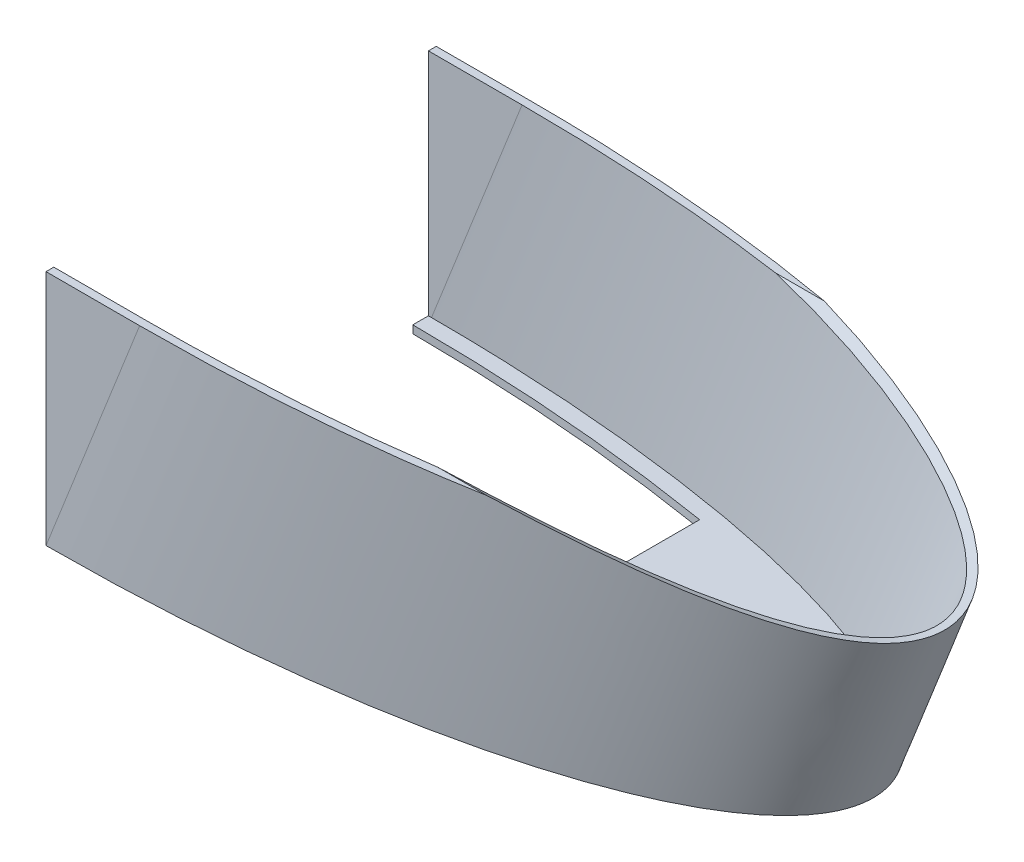
SolidWorks part; units mm, degrees
ref_plane "Front Plane" through (0, 0, 0) normal (0, 0, 1) x (1, 0, 0)
ref_plane "Top Plane" through (0, 0, 0) normal (0, 1, 0) x (1, 0, 0)
ref_plane "Right Plane" through (0, 0, 0) normal (1, 0, 0) x (0, 0, -1)
sketch "Sketch1" plane through (0, 0, 0) normal (0, 1, 0) x (1, 0, 0)
  line L1 (76.2, 38.1) -> (177.8, 38.1)
  line L3 (76.2, -38.1) -> (177.8, -38.1)
  ellipse E0 centre (76.2, 0) end of major axis (0, 0) minor radius 38.1 (76.2, 38.1) -> (76.2, -38.1) ccw
  ellipse E1 centre (177.8, 0) end of major axis (304.8, 0) minor radius 38.1 (177.8, -38.1) -> (177.8, 38.1) ccw
  point P0 (0, 0)
  dimension "D1" = 101.6
  dimension "D2" = 76.2
  dimension "D3" = 127
  dimension "D4" = 76.2
sketch "Sketch2" plane through (0, 0, 0) normal (0, 1, 0) x (1, 0, 0)
  line L2 (177.8, 39.6875) -> (177.8, 34.925)
  line L3 (177.8, -39.6875) -> (177.8, -34.925)
  line L4 (241.3, 29.7726) -> (241.3, -29.7726)
  arc A0 (177.8, 34.925) -> (241.3, 29.7726) centre (177.8, -358.9502) cw
  arc A1 (177.8, -34.925) -> (241.3, -29.7726) centre (177.8, 358.9502) ccw
  spline S0 degree 3 poles (3079.8867, 659.9165) (-414.751, 141.0277) (-37.7076, -53.2969) (210.8557, -38.4642) (218.8815, -37.7339) (234.3117, -35.8165) (241.7156, -34.6294) (255.6232, -31.8416) (262.1264, -30.241) (273.9911, -26.6816) (279.3522, -24.7233) (288.7415, -20.5076) (292.7699, -18.2517) (299.3579, -13.4802) (301.923, -10.9644) (304.5627, -6.9831) (305.2402, -5.6204) (306.1534, -2.8389) (306.3875, -1.42) (306.3875, 1.42) (306.1534, 2.8389) (305.2402, 5.6204) (304.5627, 6.9831) (301.923, 10.9644) (299.3579, 13.4802) (292.7699, 18.2517) (288.7415, 20.5076) (279.3522, 24.7233) (273.9911, 26.6816) (262.1264, 30.241) (255.6232, 31.8416) (241.7156, 34.6294) (234.3117, 35.8165) (218.8815, 37.7339) (210.8557, 38.4642) (-37.7078, 53.2969) (-414.7516, -141.028) (3079.8949, -659.9177) knots -1.773091 -1.773091 -1.773091 -1.773091 0.0625 0.0625 0.125 0.125 0.1875 0.1875 0.25 0.25 0.3125 0.3125 0.375 0.375 0.4375 0.4375 0.46875 0.46875 0.5 0.5 0.53125 0.53125 0.5625 0.5625 0.625 0.625 0.6875 0.6875 0.75 0.75 0.8125 0.8125 0.875 0.875 0.9375 0.9375 2.773092 2.773092 2.773092 2.773092 only from (177.8, -39.6875) to (177.8, 39.6875)
  spline S1 degree 3 poles (177.8, -39.6875) (186.1433, -39.6875) (194.4864, -39.441) (210.8557, -38.4642) (218.8815, -37.7339) (234.3117, -35.8165) (241.7156, -34.6294) (255.6232, -31.8416) (262.1264, -30.241) (273.9911, -26.6816) (279.3522, -24.7233) (288.7415, -20.5076) (292.7699, -18.2517) (299.3579, -13.4802) (301.923, -10.9644) (304.5627, -6.9831) (305.2402, -5.6204) (306.1534, -2.8389) (306.3875, -1.42) (306.3875, 1.42) (306.1534, 2.8389) (305.2402, 5.6204) (304.5627, 6.9831) (301.923, 10.9644) (299.3579, 13.4802) (292.7699, 18.2517) (288.7415, 20.5076) (279.3522, 24.7233) (273.9911, 26.6816) (262.1264, 30.241) (255.6232, 31.8416) (241.7156, 34.6294) (234.3117, 35.8165) (218.8815, 37.7339) (210.8557, 38.4642) (194.4864, 39.441) (186.1433, 39.6875) (177.8, 39.6875) knots 0 0 0 0 0.0625 0.0625 0.125 0.125 0.1875 0.1875 0.25 0.25 0.3125 0.3125 0.375 0.375 0.4375 0.4375 0.46875 0.46875 0.5 0.5 0.53125 0.53125 0.5625 0.5625 0.625 0.625 0.6875 0.6875 0.75 0.75 0.8125 0.8125 0.875 0.875 0.9375 0.9375 1 1 1 1
  spline S2 degree 3 poles (3082.8788, 655.6417) (-406.5374, 140.6261) (-33.3892, -48.2682) (210.4753, -33.7159) (218.4012, -32.9944) (233.6173, -31.1036) (240.9071, -29.9343) (254.5597, -27.1976) (260.9222, -25.6301) (272.4582, -22.1693) (277.6316, -20.2753) (284.3285, -17.2685) (286.3839, -16.2389) (290.1162, -14.1441) (291.7929, -13.0788) (294.7477, -10.9388) (296.0254, -9.864) (298.1723, -7.7407) (299.0409, -6.6928) (300.3862, -4.664) (300.863, -3.685) (301.4808, -1.8032) (301.625, -0.9005) (301.625, 0.9005) (301.4808, 1.8032) (300.863, 3.685) (300.3862, 4.664) (299.0409, 6.6928) (298.1723, 7.7407) (296.0254, 9.864) (294.7477, 10.9388) (291.7929, 13.0788) (290.1162, 14.1441) (286.3839, 16.2389) (284.3285, 17.2685) (277.6316, 20.2753) (272.4582, 22.1693) (260.9222, 25.6301) (254.5597, 27.1976) (240.9071, 29.9343) (233.6173, 31.1036) (218.4012, 32.9944) (210.4753, 33.7159) (-33.3908, 48.2683) (-406.5425, -140.6287) (3082.9503, -655.6522) knots -1.759473 -1.759473 -1.759473 -1.759473 0.0625 0.0625 0.125 0.125 0.1875 0.1875 0.25 0.25 0.3125 0.3125 0.34375 0.34375 0.375 0.375 0.40625 0.40625 0.4375 0.4375 0.46875 0.46875 0.5 0.5 0.53125 0.53125 0.5625 0.5625 0.59375 0.59375 0.625 0.625 0.65625 0.65625 0.6875 0.6875 0.75 0.75 0.8125 0.8125 0.875 0.875 0.9375 0.9375 2.759486 2.759486 2.759486 2.759486 only from (177.8, -34.925) to (177.8, 34.925)
  spline S3 degree 3 poles (177.8, -34.925) (186.0498, -34.925) (194.2994, -34.6812) (210.4753, -33.7159) (218.4012, -32.9944) (233.6173, -31.1036) (240.9071, -29.9343) (254.5597, -27.1976) (260.9222, -25.6301) (272.4582, -22.1693) (277.6316, -20.2753) (284.3285, -17.2685) (286.3839, -16.2389) (290.1162, -14.1441) (291.7929, -13.0788) (294.7477, -10.9388) (296.0254, -9.864) (298.1723, -7.7407) (299.0409, -6.6928) (300.3862, -4.664) (300.863, -3.685) (301.4808, -1.8032) (301.625, -0.9005) (301.625, 0.9005) (301.4808, 1.8032) (300.863, 3.685) (300.3862, 4.664) (299.0409, 6.6928) (298.1723, 7.7407) (296.0254, 9.864) (294.7477, 10.9388) (291.7929, 13.0788) (290.1162, 14.1441) (286.3839, 16.2389) (284.3285, 17.2685) (277.6316, 20.2753) (272.4582, 22.1693) (260.9222, 25.6301) (254.5597, 27.1976) (240.9071, 29.9343) (233.6173, 31.1036) (218.4012, 32.9944) (210.4753, 33.7159) (194.2994, 34.6812) (186.0498, 34.925) (177.8, 34.925) knots 0 0 0 0 0.0625 0.0625 0.125 0.125 0.1875 0.1875 0.25 0.25 0.3125 0.3125 0.34375 0.34375 0.375 0.375 0.40625 0.40625 0.4375 0.4375 0.46875 0.46875 0.5 0.5 0.53125 0.53125 0.5625 0.5625 0.59375 0.59375 0.625 0.625 0.65625 0.65625 0.6875 0.6875 0.75 0.75 0.8125 0.8125 0.875 0.875 0.9375 0.9375 1 1 1 1 construction
  dimension "D3" = 63.5
  dimension "D1" = 1.5875
  dimension "D2" = 3.175
extrude "Boss-Extrude1" add sketch "Sketch2" along normal blind 1.5875
sketch "Sketch4" plane through (0, 0, 0) normal (0, 1, 0) x (1, 0, 0)
  line L0 (177.8, 38.1) -> (177.8, 39.6875)
  line L1 (177.8, -38.1) -> (177.8, -39.6875)
  ellipse E0 centre (177.8, 0) end of major axis (50.8, 0) minor radius 38.1 (177.8, -38.1) -> (177.8, 38.1) ccw construction
  ellipse E1 centre (177.8, 0) end of major axis (50.8, 0) minor radius 38.1 (177.8, -38.1) -> (177.8, 38.1) ccw
  spline S0 degree 3 poles (2092.0188, 505.3294) (-336.1483, 102.0781) (-12.1595, -51.7723) (210.8557, -38.4642) (218.8815, -37.7339) (234.3117, -35.8165) (241.7156, -34.6294) (255.6232, -31.8416) (262.1264, -30.241) (273.9911, -26.6816) (279.3522, -24.7233) (288.7415, -20.5076) (292.7699, -18.2517) (299.3579, -13.4802) (301.923, -10.9644) (304.5627, -6.9831) (305.2402, -5.6204) (306.1534, -2.8389) (306.3875, -1.42) (306.3875, 1.42) (306.1534, 2.8389) (305.2402, 5.6204) (304.5627, 6.9831) (301.923, 10.9644) (299.3579, 13.4802) (292.7699, 18.2517) (288.7415, 20.5076) (279.3522, 24.7233) (273.9911, 26.6816) (262.1264, 30.241) (255.6232, 31.8416) (241.7156, 34.6294) (234.3117, 35.8165) (218.8815, 37.7339) (210.8557, 38.4642) (-12.1602, 51.7724) (-336.1505, -102.0791) (2092.0435, -505.3335) knots -1.577999 -1.577999 -1.577999 -1.577999 0.0625 0.0625 0.125 0.125 0.1875 0.1875 0.25 0.25 0.3125 0.3125 0.375 0.375 0.4375 0.4375 0.46875 0.46875 0.5 0.5 0.53125 0.53125 0.5625 0.5625 0.625 0.625 0.6875 0.6875 0.75 0.75 0.8125 0.8125 0.875 0.875 0.9375 0.9375 2.578005 2.578005 2.578005 2.578005 only from (177.8, -39.6875) to (177.8, 39.6875) construction
  spline S1 degree 3 poles (177.8, -39.6875) (186.1433, -39.6875) (194.4864, -39.441) (210.8557, -38.4642) (218.8815, -37.7339) (234.3117, -35.8165) (241.7156, -34.6294) (255.6232, -31.8416) (262.1264, -30.241) (273.9911, -26.6816) (279.3522, -24.7233) (288.7415, -20.5076) (292.7699, -18.2517) (299.3579, -13.4802) (301.923, -10.9644) (304.5627, -6.9831) (305.2402, -5.6204) (306.1534, -2.8389) (306.3875, -1.42) (306.3875, 1.42) (306.1534, 2.8389) (305.2402, 5.6204) (304.5627, 6.9831) (301.923, 10.9644) (299.3579, 13.4802) (292.7699, 18.2517) (288.7415, 20.5076) (279.3522, 24.7233) (273.9911, 26.6816) (262.1264, 30.241) (255.6232, 31.8416) (241.7156, 34.6294) (234.3117, 35.8165) (218.8815, 37.7339) (210.8557, 38.4642) (194.4864, 39.441) (186.1433, 39.6875) (177.8, 39.6875) knots 0 0 0 0 0.0625 0.0625 0.125 0.125 0.1875 0.1875 0.25 0.25 0.3125 0.3125 0.375 0.375 0.4375 0.4375 0.46875 0.46875 0.5 0.5 0.53125 0.53125 0.5625 0.5625 0.625 0.625 0.6875 0.6875 0.75 0.75 0.8125 0.8125 0.875 0.875 0.9375 0.9375 1 1 1 1
sketch "Sketch5" plane through (0, 0, 0) normal (0, 0, 1) x (1, 0, 0)
  line L0 (306.3875, 0) -> (325.4375, 48.26)
  point P2 (306.3875, 0)
  point P6 (312.8027, 1.5875)
  dimension "D1" = 19.05
  dimension "D2" = 48.26
sweep "Sweep1" add profiles "Sketch4" path "Sketch5"
ref_plane "Plane1" through (0, 0, -38.1) normal (0, 0, 1) x (1, 0, 0)
sketch "Sketch7" plane through (0, 0, -38.1) normal (0, 0, 1) x (1, 0, 0)
  line L0 (177.8, 0) -> (196.85, 48.26)
  line L1 (196.85, 48.26) -> (177.8, 48.26)
  line L2 (177.8, 48.26) -> (177.8, 0)
  point P5 (177.8, 0)
extrude "Boss-Extrude3" add sketch "Sketch7" against normal blind 1.5875
mirror "Mirror2" about plane through (0, 0, 0) normal (0, 0, 1) of "Boss-Extrude3"
sketch "Sketch8" plane through (0, 0, 0) normal (1, 0, 0) x (0, 0, -1)
  line L0 (38.1, 0) -> (-38.1, 0) construction
  circle A0 centre (0, 93.98) radius 57.15
  point P4 (0, 102.87)
  point P5 (0, 0)
  dimension "D1" = 93.98
  dimension "D2" = 114.3
extrude "Cut-Extrude2" cut sketch "Sketch8" along normal through all
hole_wizard "CSK for #6 Flat Head Socket Cap Screw1" positions "Sketch9" profile "Sketch10" countersink size "#6" standard "ANSI Inch"
sketch "Sketch9" plane through (0, 0, 0) normal (0, -1, 0) x (-1, 0, 0)
  point P0 (-273.05, 0)
  point P4 (0, 0)
  dimension "D1" = 31.75
sketch "Sketch10" plane through (273.05, 0, 0) normal (1, 0, 0) x (0, 0, -1)
  line L0 (0, 0) -> (0, 26.5408)
  line L1 (0, 26.5408) -> (1.8986, 25.4)
  line L2 (1.8986, 25.4) -> (1.8986, 2.301)
  line L3 (1.8986, 2.301) -> (3.8989, 0)
  line L5 (3.8989, 0) -> (0, 0)
  line L6 (-1.8986, 2.301) -> (-3.8989, 0) construction
  line L10 (0, 26.5408) -> (-1.8987, 25.4) construction
  line L11 (0, -6.35) -> (0, 107.95) construction
  dimension "Hole Dia." = 3.7973
  dimension "Hole Depth" = 25.4
  dimension "Near C'Sink Dia." = 7.7978
  dimension "Near C'Sink Angle" = 82
  dimension "Drill Angle" = 118
